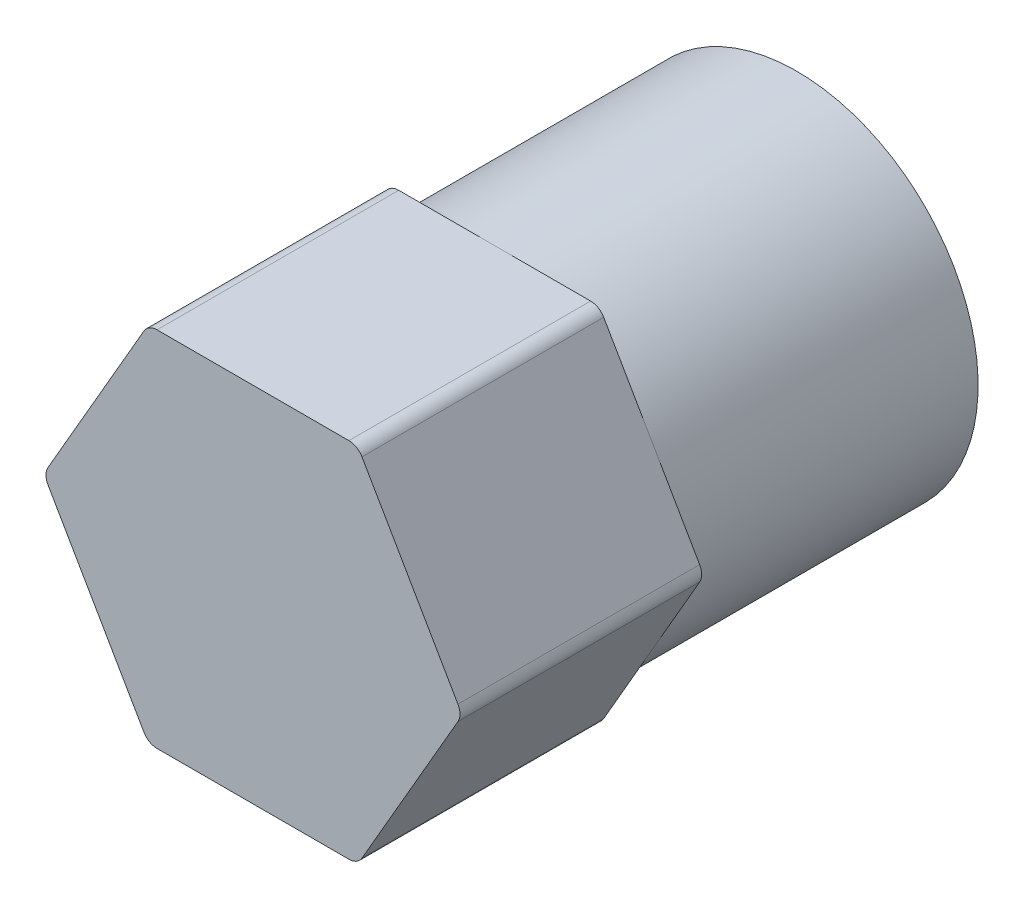
SolidWorks part; units mm, degrees
ref_plane "Front Plane" through (0, 0, 0) normal (0, 0, 1) x (1, 0, 0)
ref_plane "Top Plane" through (0, 0, 0) normal (0, 1, 0) x (1, 0, 0)
ref_plane "Right Plane" through (0, 0, 0) normal (1, 0, 0) x (0, 0, -1)
sketch "Sketch1" plane through (0, 0, 0) normal (0, 0, 1) x (1, 0, 0)
  line L0 (-3.4641, -6) -> (3.4641, -6)
  line L1 (3.4641, 6) -> (6.9282, 0)
  line L2 (6.9282, 0) -> (3.4641, -6)
  line L5 (-3.4641, 6) -> (3.4641, 6)
  line L7 (-3.4641, 6) -> (-6.9282, 0)
  line L8 (-6.9282, 0) -> (-3.4641, -6)
  point P6 (0, -6)
extrude "Boss-Extrude1" add sketch "Sketch1" along normal blind 8
sketch "Sketch2" plane through (0, 0, 0) normal (0, 0, -1) x (-1, 0, 0)
  circle A0 centre (0, 0) radius 6
extrude "Boss-Extrude2" add sketch "Sketch2" along normal blind 10
sketch "Sketch3" plane through (0, 0, -10) normal (0, 0, -1) x (-1, 0, 0)
  line L0 (-1.35, 1.4756) -> (1.35, 1.4756)
  arc A0 (-1.35, 1.4756) -> (1.35, 1.4756) centre (0, 0) ccw
extrude "Cut-Extrude1" cut sketch "Sketch3" against normal blind 8
fillet "Fillet1" radius 0.5 6 edges at (-6.9282, 0, 4) (-3.4641, -6, 4) (3.4641, -6, 4) (6.9282, 0, 4) (3.4641, 6, 4) (-3.4641, 6, 4)
